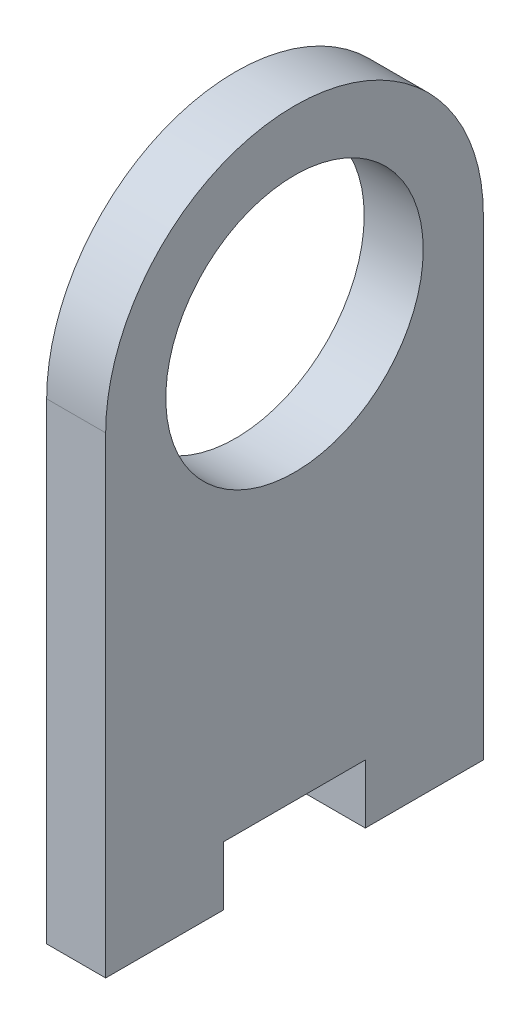
SolidWorks part; units mm, degrees
ref_plane "Front" through (0, 0, 0) normal (0, 0, 1) x (1, 0, 0)
ref_plane "Top" through (0, 0, 0) normal (0, 1, 0) x (1, 0, 0)
ref_plane "Right" through (0, 0, 0) normal (1, 0, 0) x (0, 0, -1)
sketch "Sketch1" plane through (0, 0, 0) normal (1, 0, 0) x (0, 0, -1)
  line L0 (27.94, 0) -> (40.64, 0)
  line L1 (0, 0) -> (12.7, 0)
  line L2 (0, 0) -> (0, 50.8)
  line L4 (40.64, 0) -> (40.64, 50.8)
  line L5 (12.7, 0) -> (12.7, 6.35)
  line L6 (12.7, 6.35) -> (27.94, 6.35)
  line L7 (27.94, 0) -> (27.94, 6.35)
  arc A0 (0, 50.8) -> (40.64, 50.8) centre (20.32, 50.8) cw
  circle A1 centre (20.32, 50.8) radius 13.85
  dimension "D2" = 27.7
  dimension "D3" = 15.24
  dimension "D1" = 6.35
  dimension "D4" = 50.8
  dimension "D5" = 12.7
extrude "Boss-Extrude1" add sketch "Sketch1" along normal blind 6.35
